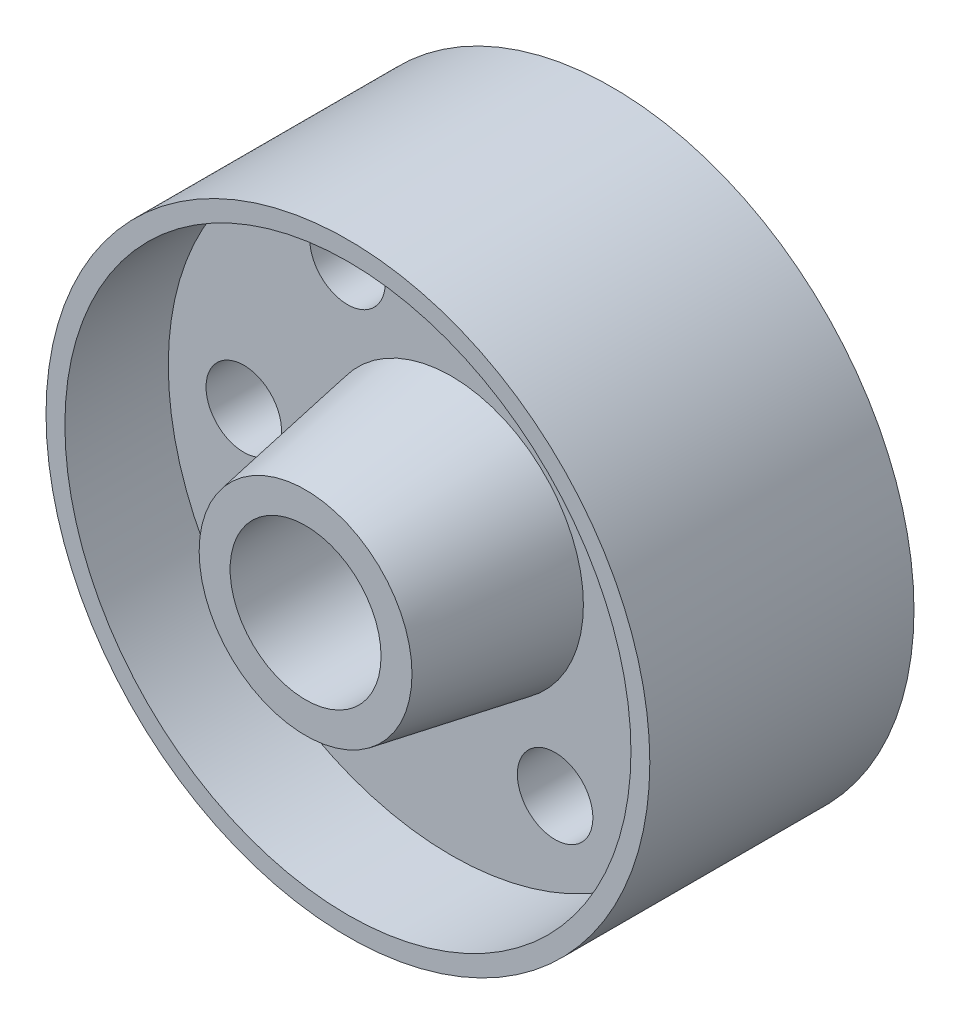
SolidWorks part; units mm, degrees
material "Plain Carbon Steel"
ref_plane "Front Plane" through (0, 0, 0) normal (0, 0, 1) x (1, 0, 0)
ref_plane "Top Plane" through (0, 0, 0) normal (0, 1, 0) x (1, 0, 0)
ref_plane "Right Plane" through (0, 0, 0) normal (1, 0, 0) x (0, 0, -1)
sketch "Sketch1" plane through (0, 0, 0) normal (1, 0, 0) x (0, 0, -1)
  line L0 (-29.3497, 12.7) -> (29.3497, 12.7)
  line L1 (-29.3497, 12.7) -> (-29.3497, 17.907)
  line L2 (29.3497, 12.7) -> (29.3497, 17.907)
  line L3 (-29.3497, 17.907) -> (-4.826, 22.225)
  line L4 (-4.826, 22.225) -> (-4.826, 47.625)
  line L5 (-4.826, 47.625) -> (-22.225, 47.625)
  line L6 (-22.225, 47.625) -> (-22.225, 50.8)
  line L7 (-22.225, 50.8) -> (22.225, 50.8)
  line L8 (22.225, 50.8) -> (22.225, 47.625)
  line L9 (22.225, 47.625) -> (4.826, 47.625)
  line L10 (4.826, 47.625) -> (4.826, 22.225)
  line L11 (4.826, 22.225) -> (29.3497, 17.907)
  line L12 (-50.3329, 0) -> (56.4627, 0) construction
  point P16 (0, 12.7)
  point P22 (0, 50.8)
  dimension "D1" = 58.6994
  dimension "D2" = 9.652
  dimension "D3" = 44.45
  dimension "D4" = 3.175
  dimension "D5" = 12.7
  dimension "D6" = 17.907
  dimension "D7" = 22.225
  dimension "D8" = 47.625
revolve "Revolve1" add sketch "Sketch1" angle 360 about L12
hole_wizard "3/8 (0.5) Diameter Hole1" positions "Sketch2" profile "Sketch3" hole size "3/8" standard "ANSI Inch" end condition through all
sketch "Sketch2" plane through (0, 0, 4.826) normal (0, 0, 1) x (1, 0, 0)
  circle A0 centre (0, 0) radius 34.925 construction
  point P0 (34.925, 0)
  point P8 (13.1412, 32.3584)
  point P9 (34.925, 0)
  dimension "D1" = 69.85
sketch "Sketch3" plane through (34.925, 0, 4.826) normal (1, 0, 0) x (0, -1, 0)
  line L0 (0, 0) -> (0, 34.1757)
  line L1 (0, 34.1757) -> (6.35, 34.1757)
  line L2 (6.35, 34.1757) -> (6.35, 0)
  line L5 (6.35, 0) -> (0, 0)
  line L11 (0, -6.35) -> (0, 107.95) construction
  dimension "Thru Hole Dia." = 12.7
  dimension "Thru Hole Depth" = 34.1757
pattern_circular "CirPattern1" count 6 over 360 about axis through (0, 0, 0) along (0, 0, 1) of "3/8 (0.5) Diameter Hole1"
